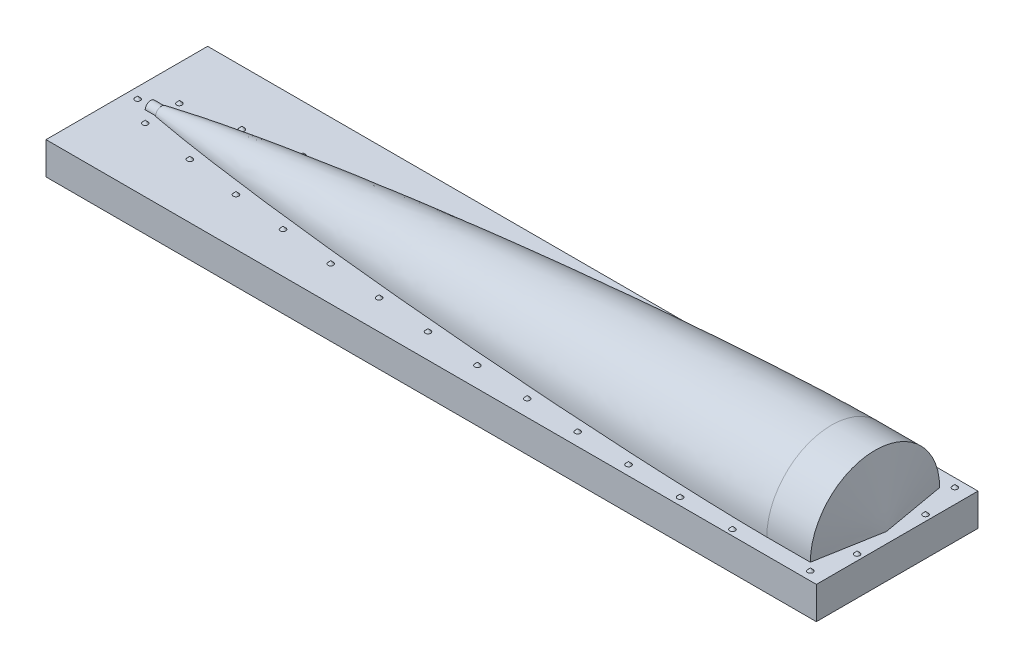
SolidWorks part; units mm, degrees
ref_plane "Front Plane" through (0, 0, 0) normal (0, 0, 1) x (1, 0, 0)
ref_plane "Top Plane" through (0, 0, 0) normal (0, 1, 0) x (1, 0, 0)
ref_plane "Right Plane" through (0, 0, 0) normal (1, 0, 0) x (0, 0, -1)
sketch "Sketch4" plane through (0, 0, 0) normal (0, 1, 0) x (1, 0, 0)
  line L0 (805.088, 76.204) -> (856.4344, 76.204)
  line L1 (856.4344, 76.204) -> (869.8712, 0)
  line L2 (0, 0) -> (869.8712, 0) construction
  line L3 (15.3303, 6.35) -> (2.6303, 6.35)
  line L4 (15.3303, 6.35) -> (15.4751, 7.0222)
  line L5 (2.6303, 6.35) -> (0, 0)
  line L6 (0, 0) -> (869.8712, 0)
  line L7 (15.4751, 7.0222) -> (15.4751, 0) construction
  spline S0 degree 4 poles (-32.8228, -5.2818) (-32.7359, -5.2278) (-32.56, -5.1232) (-32.2558, -4.9583) (-31.7935, -4.7306) (-31.1786, -4.4525) (-30.2745, -4.0766) (-28.8842, -3.5495) (-26.638, -2.7774) (-23.736, -1.8839) (-20.3525, -0.927) (-16.0942, 0.191) (-11.461, 1.3336) (-6.3356, 2.5174) (-1.0274, 3.686) (4.4, 4.8234) (9.0775, 5.7764) (14.3053, 6.8002) (17.9387, 7.4962) (22.9566, 8.4381) (27.9637, 9.3543) (34.059, 10.4426) (42.5737, 11.9174) (52.8462, 13.6363) (63.0528, 15.2769) (73.2792, 16.8659) (83.4933, 18.412) (93.7695, 19.9301) (105.7981, 21.656) (119.5916, 23.5726) (133.4376, 25.4388) (147.2917, 27.2534) (161.1513, 29.0199) (178.4833, 31.1721) (199.2917, 33.6706) (223.5817, 36.473) (247.8854, 39.1524) (268.726, 41.3678) (289.573, 43.5213) (310.4261, 45.6146) (334.7632, 47.9726) (362.5874, 50.5567) (390.4214, 53.0336) (418.2645, 55.4058) (446.1162, 57.675) (473.976, 59.842) (501.8436, 61.9065) (536.6874, 64.358) (578.5144, 67.0891) (627.3327, 69.9553) (672.6856, 72.2223) (707.5846, 73.6979) (732.0197, 74.5805) (745.9842, 75.0371) (761.2267, 75.4786) (775.3635, 75.8182) (788.3941, 76.0618) (797.9332, 76.1725) (802.703, 76.204) (805.088, 76.204) knots 0 0 0 0 0 0.000486 0.000971 0.00164 0.002446 0.003683 0.005621 0.008681 0.013732 0.018047 0.022362 0.029461 0.036561 0.042644 0.048727 0.05481 0.060892 0.065035 0.069177 0.077462 0.085747 0.094032 0.110376 0.12672 0.134892 0.143064 0.159409 0.175978 0.192548 0.209117 0.225687 0.242256 0.258826 0.291965 0.325104 0.358243 0.374813 0.391382 0.424521 0.45766 0.490799 0.523939 0.557078 0.590217 0.623356 0.656495 0.689634 0.755912 0.82219 0.888468 0.905038 0.921608 0.938177 0.954747 0.977373 0.988687 1 1 1 1 1 construction
  spline S1 degree 4 poles (15.4751, 7.0222) (15.8237, 7.0894) (16.9759, 7.3107) (18.8944, 7.6756) (22.9566, 8.4381) (27.9637, 9.3543) (34.059, 10.4426) (42.5737, 11.9174) (52.8462, 13.6363) (63.0528, 15.2769) (73.2792, 16.8659) (83.4933, 18.412) (93.7695, 19.9301) (105.7981, 21.656) (119.5916, 23.5726) (133.4376, 25.4388) (147.2917, 27.2534) (161.1513, 29.0199) (178.4833, 31.1721) (199.2917, 33.6706) (223.5817, 36.473) (247.8854, 39.1524) (268.726, 41.3678) (289.573, 43.5213) (310.4261, 45.6146) (334.7632, 47.9726) (362.5874, 50.5567) (390.4214, 53.0336) (418.2645, 55.4058) (446.1162, 57.675) (473.976, 59.842) (501.8436, 61.9065) (536.6874, 64.358) (578.5144, 67.0891) (627.3327, 69.9553) (672.6856, 72.2223) (707.5846, 73.6979) (732.0197, 74.5805) (745.9842, 75.0371) (761.2267, 75.4786) (775.3635, 75.8182) (788.3941, 76.0618) (797.9332, 76.1725) (802.703, 76.204) (805.088, 76.204) knots 0.059124 0.059124 0.059124 0.059124 0.059124 0.060892 0.065035 0.069177 0.077462 0.085747 0.094032 0.110376 0.12672 0.134892 0.143064 0.159409 0.175978 0.192548 0.209117 0.225687 0.242256 0.258826 0.291965 0.325104 0.358243 0.374813 0.391382 0.424521 0.45766 0.490799 0.523939 0.557078 0.590217 0.623356 0.656495 0.689634 0.755912 0.82219 0.888468 0.905038 0.921608 0.938177 0.954747 0.977373 0.988687 1 1 1 1 1
  point P6 (0, 0)
  dimension "D1" = 869.8712
  dimension "D2" = 12.7
  dimension "D3" = 102.157
  dimension "D4" = 80
  dimension "D5" = 51.3464
  dimension "D6" = 76.204
  dimension "D7" = 6.35
  dimension "D8" = 67.5
revolve "Revolve1" add sketch "Sketch4" angle 180 about L2
sketch "Sketch5" plane through (0, 0, 0) normal (0, -1, 0) x (1, 0, 0)
  line L0 (-25.4, 95.254) -> (-25.4, -95.254)
  line L1 (856.4344, -76.204) -> (805.088, -76.204) construction
  line L2 (856.4344, 76.204) -> (805.088, 76.204) construction
  line L3 (-25.4, -95.254) -> (882.5712, -95.254)
  line L6 (-25.4, 95.254) -> (882.5712, 95.254)
  line L7 (882.5712, 95.254) -> (882.5712, -95.254)
  dimension "D1" = 12.7
  dimension "D2" = 19.05
  dimension "D3" = 19.05
  dimension "D4" = 25.4
extrude "Boss-Extrude1" add sketch "Sketch5" along normal blind 38.1
sketch "Sketch8" plane through (0, 0, 0) normal (0, 1, 0) x (1, 0, 0)
  line L0 (18.8271, -7.6614) -> (16.4703, -20.1408) construction
  line L1 (144.3669, -26.8641) -> (142.7299, -39.4582) construction
  line L2 (270.5156, -41.544) -> (269.1931, -54.175) construction
  line L3 (396.9443, -53.5768) -> (395.8535, -66.2299) construction
  line L4 (523.5622, -63.4216) -> (522.6843, -76.0912) construction
  line L5 (650.3322, -71.06) -> (649.691, -83.7438) construction
  line L6 (777.2422, -75.8406) -> (776.9801, -88.5379) construction
  line L7 (863.1528, -38.102) -> (875.6598, -40.3073) construction
  line L8 (869.8712, 0) -> (856.4344, -76.204) construction
  line L9 (856.4344, -76.204) -> (865.4146, -85.1842) construction
  line L10 (856.4344, -76.204) -> (805.088, -76.204) construction
  line L11 (0, 0) -> (-12.7, 0) construction
  line L12 (856.4344, 76.204) -> (865.4146, 85.1842) construction
  line L13 (863.1528, 38.102) -> (875.6598, 40.3073) construction
  line L14 (777.2422, 75.8406) -> (776.9801, 88.5379) construction
  line L15 (650.3322, 71.06) -> (649.691, 83.7438) construction
  line L16 (523.5622, 63.4216) -> (522.6843, 76.0912) construction
  line L17 (396.9443, 53.5768) -> (395.8535, 66.2299) construction
  line L18 (270.5156, 41.544) -> (269.1931, 54.175) construction
  line L19 (144.3669, 26.8641) -> (142.7299, 39.4582) construction
  line L20 (18.8271, 7.6614) -> (16.4703, 20.1408) construction
  line L21 (882.5712, 95.254) -> (882.5712, -95.254) construction
  line L22 (81.463, -18.1012) -> (79.5772, -30.6604) construction
  line L23 (81.463, 18.1012) -> (79.5772, 30.6604) construction
  line L24 (207.3949, -34.5923) -> (205.9327, -47.2078) construction
  line L25 (333.7019, -47.8486) -> (332.5003, -60.4916) construction
  line L26 (460.2321, -58.7644) -> (459.2475, -71.4262) construction
  line L27 (586.9288, -67.5346) -> (586.1629, -80.2115) construction
  line L28 (713.7685, -73.9037) -> (713.2788, -86.5943) construction
  line L29 (713.7685, 73.9037) -> (713.2788, 86.5943) construction
  line L30 (586.9288, 67.5346) -> (586.1629, 80.2115) construction
  line L31 (460.2321, 58.7644) -> (459.2475, 71.4262) construction
  line L32 (333.7019, 47.8486) -> (332.5003, 60.4916) construction
  line L33 (207.3949, 34.5923) -> (205.9327, 47.2078) construction
  line L61 (0, 0) -> (882.5712, 0) construction
  circle A0 centre (16.4703, -20.1408) radius 3.175
  circle A1 centre (142.7299, -39.4582) radius 3.175
  circle A2 centre (269.1931, -54.175) radius 3.175
  circle A3 centre (395.8535, -66.2299) radius 3.175
  circle A4 centre (522.6843, -76.0912) radius 3.175
  circle A5 centre (649.691, -83.7438) radius 3.175
  circle A6 centre (776.9801, -88.5379) radius 3.175
  circle A7 centre (875.6598, -40.3073) radius 3.175
  circle A8 centre (865.4146, -85.1842) radius 3.175
  circle A9 centre (-12.7, 0) radius 3.175
  circle A10 centre (865.4146, 85.1842) radius 3.175
  circle A11 centre (875.6598, 40.3073) radius 3.175
  circle A12 centre (776.9801, 88.5379) radius 3.175
  circle A13 centre (649.691, 83.7438) radius 3.175
  circle A14 centre (522.6843, 76.0912) radius 3.175
  circle A15 centre (395.8535, 66.2299) radius 3.175
  circle A16 centre (269.1931, 54.175) radius 3.175
  circle A17 centre (142.7299, 39.4582) radius 3.175
  circle A18 centre (16.4703, 20.1408) radius 3.175
  circle A19 centre (79.5772, -30.6604) radius 3.175
  circle A20 centre (79.5772, 30.6604) radius 3.175
  circle A21 centre (205.9327, -47.2078) radius 3.175
  circle A22 centre (332.5003, -60.4916) radius 3.175
  circle A23 centre (459.2475, -71.4262) radius 3.175
  circle A24 centre (586.1629, -80.2115) radius 3.175
  circle A25 centre (713.2788, -86.5943) radius 3.175
  circle A26 centre (713.2788, 86.5943) radius 3.175
  circle A27 centre (586.1629, 80.2115) radius 3.175
  circle A28 centre (459.2475, 71.4262) radius 3.175
  circle A29 centre (332.5003, 60.4916) radius 3.175
  circle A30 centre (205.9327, 47.2078) radius 3.175
  spline S3 degree 4 poles (805.088, -76.204) (802.703, -76.204) (797.9332, -76.1725) (788.3941, -76.0618) (775.3635, -75.8182) (761.2267, -75.4786) (745.9842, -75.0371) (732.0197, -74.5805) (707.5846, -73.6979) (672.6856, -72.2223) (627.3327, -69.9553) (578.5144, -67.0891) (536.6874, -64.358) (501.8436, -61.9065) (473.976, -59.842) (446.1162, -57.675) (418.2645, -55.4058) (390.4214, -53.0336) (362.5874, -50.5567) (334.7632, -47.9726) (310.4261, -45.6146) (289.573, -43.5213) (268.726, -41.3678) (247.8854, -39.1524) (223.5817, -36.473) (199.2917, -33.6706) (178.4833, -31.1721) (161.1513, -29.0199) (147.2917, -27.2534) (133.4376, -25.4388) (119.5916, -23.5726) (105.7981, -21.656) (93.7695, -19.9301) (83.4933, -18.412) (73.2792, -16.8659) (63.0528, -15.2769) (52.8462, -13.6363) (42.5737, -11.9174) (34.059, -10.4426) (27.9637, -9.3543) (22.9566, -8.4381) (18.8944, -7.6756) (16.9759, -7.3107) (15.8237, -7.0894) (15.4751, -7.0222) knots 0.059124 0.059124 0.059124 0.059124 0.059124 0.070437 0.081751 0.104377 0.120947 0.137516 0.154086 0.170655 0.236934 0.303212 0.36949 0.402629 0.435768 0.468907 0.502046 0.535185 0.568324 0.601463 0.634603 0.667742 0.684311 0.700881 0.73402 0.767159 0.800298 0.816868 0.833437 0.850007 0.866576 0.883146 0.899715 0.916059 0.924232 0.932404 0.948748 0.965092 0.973377 0.981662 0.989947 0.994089 0.998231 1 1 1 1 1 construction
  dimension "D1" = 12.7
  dimension "D2" = 6.35
  dimension "D4" = 127
  dimension "D7" = 63.5
  dimension "D10" = 63.5
  dimension "D13" = 63.5
  dimension "D9" = 63.5
  dimension "D3" = 127
  dimension "D5" = 127
  dimension "D6" = 135
  dimension "D8" = 127
  dimension "D11" = 127
  dimension "D12" = 63.5
  dimension "D14" = 127
  dimension "D15" = 63.5
extrude "Boss-Extrude3" add sketch "Sketch8" along normal blind 6.35 draft 45
draft "Draft3" [suppressed] type of draft neutral plane draft angle 45 faces to draft 18 parameters "D1"=45
